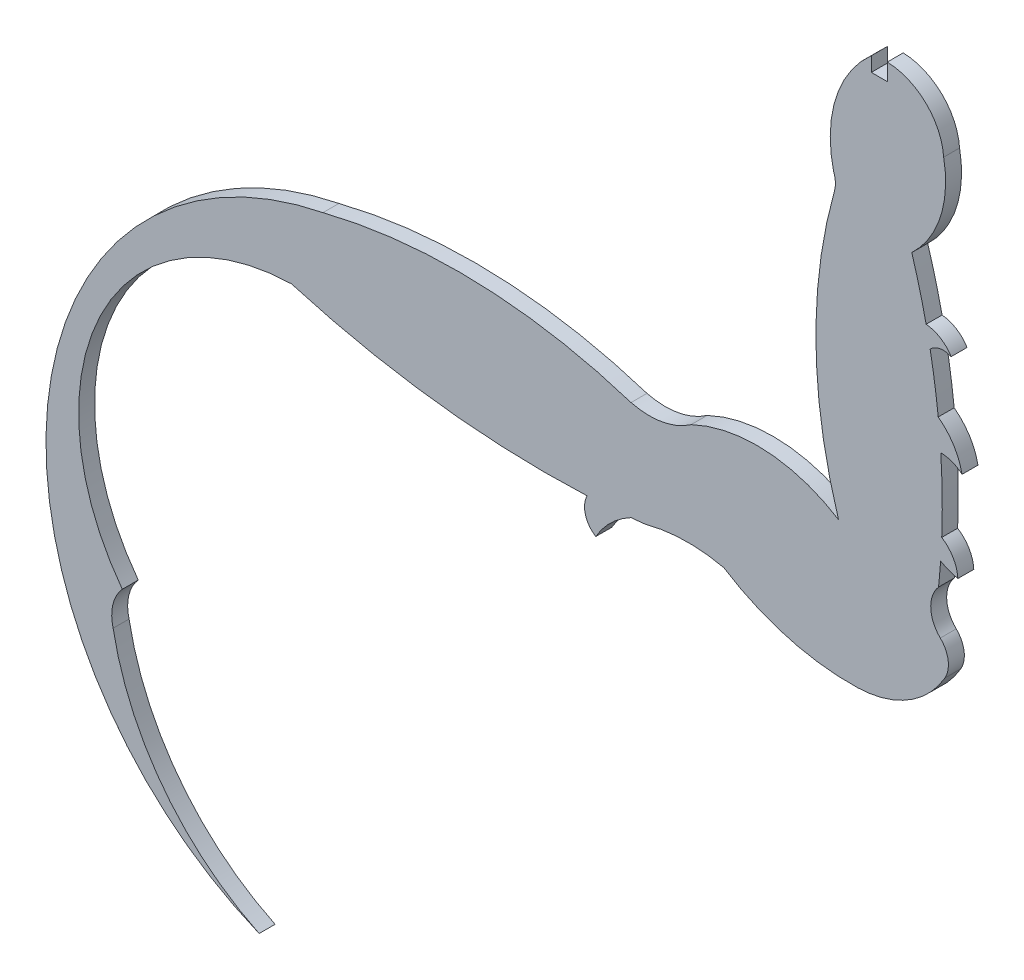
SolidWorks part; units mm, degrees
ref_plane "Front Plane" through (0, 0, 0) normal (0, 0, 1) x (1, 0, 0)
ref_plane "Top Plane" through (0, 0, 0) normal (0, 1, 0) x (1, 0, 0)
ref_plane "Right Plane" through (0, 0, 0) normal (1, 0, 0) x (0, 0, -1)
sketch "Sketch1" plane through (0, 0, 0) normal (0, 0, 1) x (1, 0, 0)
  line L3 (-1.524, 93.9963) -> (0, 93.9963)
  line L4 (0, 93.9963) -> (0, 95.6149)
  line L5 (-1.524, 93.9963) -> (-1.524, 95.3808)
  arc A0 (-1.524, 95.3808) -> (-5.1352, 83.9984) centre (6.107, 86.6957) ccw
  arc A1 (3.7192, 75.7566) -> (6.107, 74.2642) centre (3.4352, 72.6457) cw
  arc A2 (-5.0554, 82.3833) -> (-4.6596, 55.3804) centre (40.5076, 69.5468) ccw
  arc A3 (-5.1352, 83.9984) -> (-5.0554, 82.3833) centre (-7.5002, 83.0721) cw
  arc A4 (0, 95.6149) -> (5.3943, 90.432) centre (-0.1739, 90.0353) cw
  arc A5 (5.3943, 90.432) -> (2.3445, 81.0105) centre (-4.6596, 88.4821) cw
  arc A6 (2.3445, 81.0105) -> (3.7192, 75.7566) centre (-61.5546, 61.4842) cw
  arc A7 (4.9034, 54.5771) -> (5.0729, 50.4429) centre (7.1548, 52.5988) ccw
  arc A8 (5.5108, 47.3503) -> (-2.8177, 42.3742) centre (-3.094, 52.2944) cw
  arc A9 (5.0729, 50.4429) -> (5.5108, 47.3503) centre (3.3084, 48.6157) cw
  arc A10 (-2.8177, 42.3742) -> (-15.6389, 45.9204) centre (-3.449, 65.042) cw
  arc A11 (-15.6389, 45.9204) -> (-23.1281, 45.7653) centre (-19.0709, 30.7507) ccw
  arc A12 (-23.1281, 45.7653) -> (-24.5068, 45.6247) centre (-32.6045, 131.8147) cw
  arc A13 (-4.6596, 55.3804) -> (-18.7504, 56.2078) centre (-12.4542, 43.035) ccw
  arc A14 (-18.7504, 56.2078) -> (-24.5068, 55.1579) centre (-22.7617, 61.8956) cw
  arc A15 (-24.5068, 55.1579) -> (-53.9706, 56.1576) centre (-40.977, 4.428) ccw
  arc A16 (-53.9706, 56.1576) -> (-60.0772, -6.6073) centre (-47.523, 23.8508) ccw
  arc A17 (-56.9935, 48.7516) -> (-73.1639, 15.3642) centre (-56.4778, 27.8923) ccw
  arc A18 (-73.1639, 15.3642) -> (-74.0422, 11.6993) centre (-70.2308, 12.7236) ccw
  arc A19 (-74.0422, 11.6993) -> (-60.0772, -6.6073) centre (-48.9408, 16.3678) ccw
  arc A20 (6.107, 74.2642) -> (4.1005, 73.8852) centre (5.3696, 72.6671) ccw
  arc A21 (4.8756, 68.6536) -> (7.1548, 65.042) centre (1.3105, 63.8787) cw
  arc A22 (7.1548, 65.042) -> (5.1208, 65.8153) centre (5.0446, 62.553) ccw
  arc A23 (5.2092, 58.8439) -> (6.7514, 56.2078) centre (3.4376, 56.0382) cw
  arc A24 (6.7514, 56.2078) -> (5.0994, 56.8354) centre (7.9732, 61.9119) cw
  arc A25 (5.0994, 56.8354) -> (4.9034, 54.5771) centre (-61.5546, 61.4842) cw
  arc A26 (5.1208, 65.8153) -> (5.2092, 58.8439) centre (-61.5546, 61.4842) cw
  arc A27 (4.1005, 73.8852) -> (4.8756, 68.6536) centre (-61.5546, 61.4842) cw
  arc A28 (-24.5068, 45.6247) -> (-27.8791, 42.3742) centre (-20.6561, 38.2549) ccw
  arc A29 (-27.8791, 42.3742) -> (-28.7078, 45.3329) centre (-26.6887, 44.303) cw
  arc A30 (-28.7078, 45.3329) -> (-56.9935, 48.7516) centre (-32.6045, 131.8147) cw
  dimension "D1" = 2.54
  dimension "D2" = 2.54
extrude "Boss-Extrude1" add sketch "Sketch1" along normal blind 1.524
